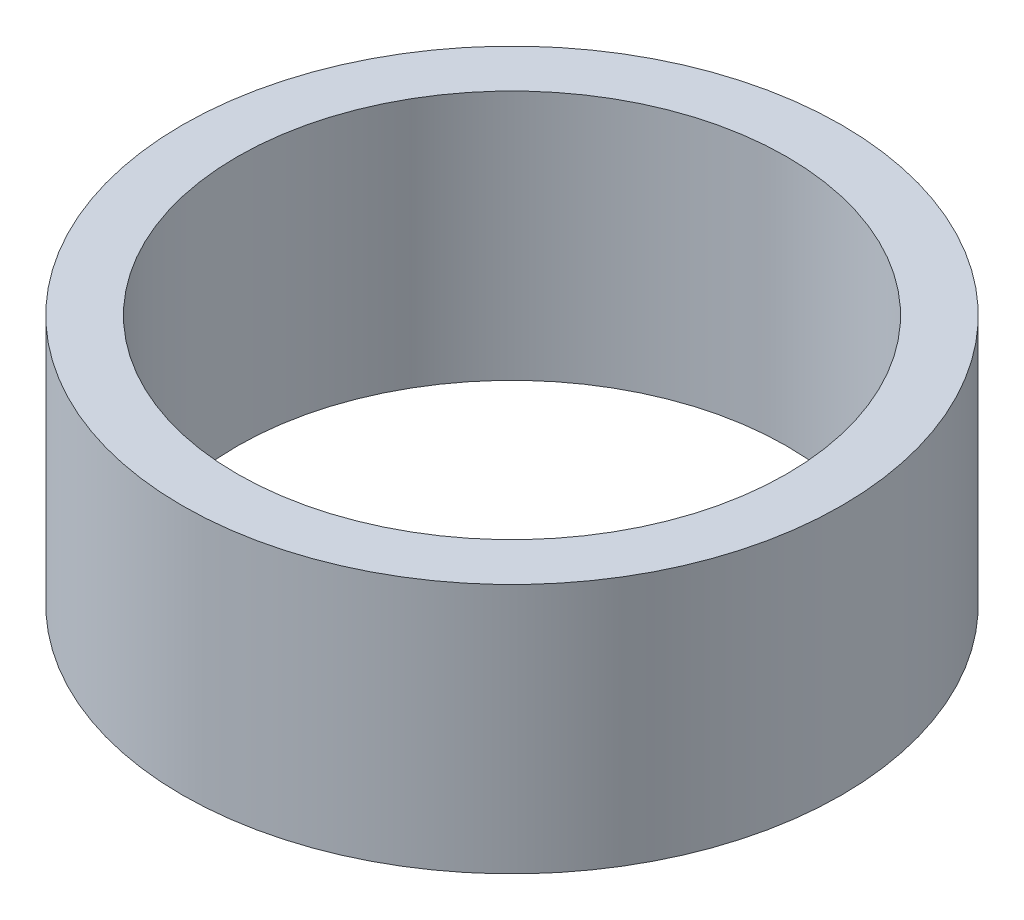
SolidWorks part; units mm, degrees
ref_plane "Front Plane" through (0, 0, 0) normal (0, 0, 1) x (1, 0, 0)
ref_plane "Top Plane" through (0, 0, 0) normal (0, 1, 0) x (1, 0, 0)
ref_plane "Right Plane" through (0, 0, 0) normal (1, 0, 0) x (0, 0, -1)
sketch "Sketch2" plane through (0, 0, 0) normal (0, 1, 0) x (1, 0, 0)
  circle A0 centre (0, 0) radius 2.5
  circle A1 centre (0, 0) radius 3
  dimension "D1" = 0.5
  dimension "D2" = 5
extrude "Boss-Extrude1" add sketch "Sketch2" along normal blind 2.28
